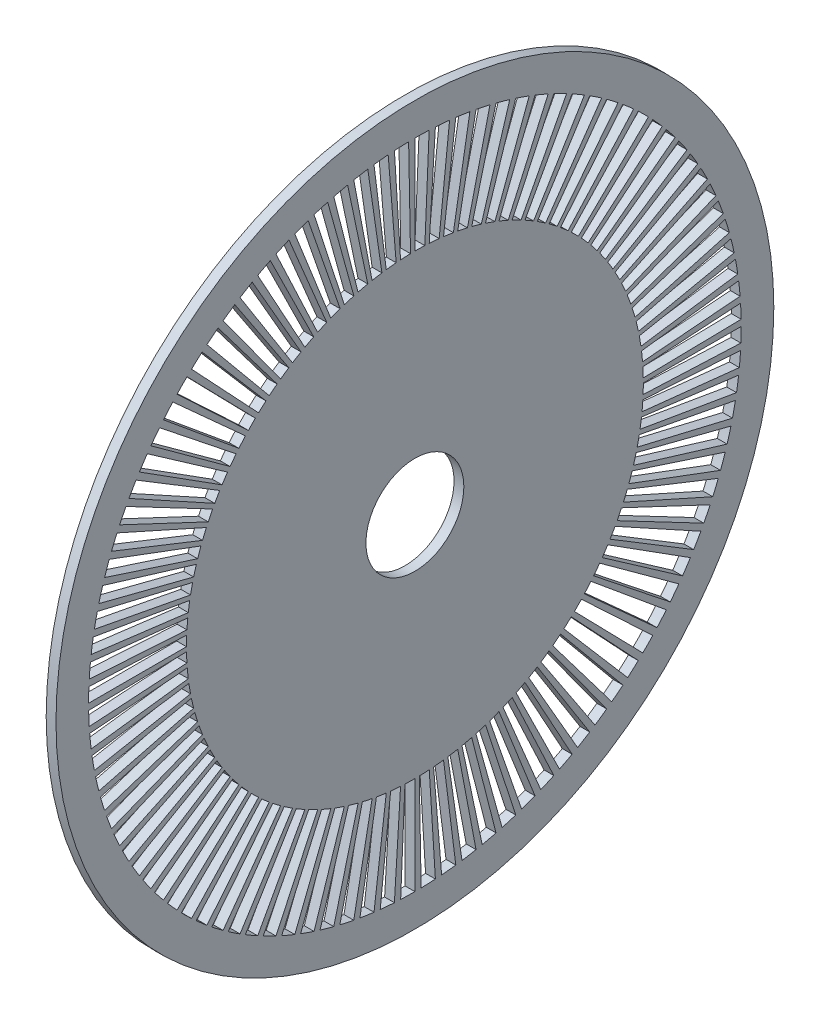
SolidWorks part; units mm, degrees
material "AISI 1020"
ref_plane "Plan de face" through (0, 0, 0) normal (0, 0, 1) x (1, 0, 0)
ref_plane "Plan de dessus" through (0, 0, 0) normal (0, 1, 0) x (1, 0, 0)
ref_plane "Plan de droite" through (0, 0, 0) normal (1, 0, 0) x (0, 0, -1)
sketch "Esquisse1" plane through (0, 0, 0) normal (1, 0, 0) x (0, 0, -1)
  line L0 (0, 0) -> (0, 11) construction
  line L1 (0, 0) -> (0.6907, 10.9783) construction
  line L2 (0, 7) -> (0, 10)
  line L3 (0.3053, 6.9933) -> (0.4362, 9.9905)
  line L4 (0, 0) -> (0.4798, 10.9895) construction
  line L5 (0.7438, 6.9604) -> (1.0626, 9.9434)
  line L6 (0.4395, 6.9862) -> (0.6279, 9.9803)
  line L7 (1.1794, 6.8999) -> (1.6849, 9.857)
  line L8 (0.8773, 6.9448) -> (1.2533, 9.9211)
  line L9 (1.6103, 6.8123) -> (2.3005, 9.7318)
  line L10 (1.3117, 6.876) -> (1.8738, 9.8229)
  line L11 (2.0349, 6.6977) -> (2.907, 9.5681)
  line L12 (1.7408, 6.7801) -> (2.4869, 9.6858)
  line L13 (2.4515, 6.5567) -> (3.5021, 9.3667)
  line L14 (2.1631, 6.6574) -> (3.0902, 9.5106)
  line L15 (2.8583, 6.3898) -> (4.0833, 9.1283)
  line L16 (2.5769, 6.5084) -> (3.6812, 9.2978)
  line L17 (3.2539, 6.1978) -> (4.6484, 8.8539)
  line L18 (2.9805, 6.3338) -> (4.2578, 9.0483)
  line L19 (3.6366, 5.9812) -> (5.1952, 8.5446)
  line L20 (3.3723, 6.1341) -> (4.8175, 8.7631)
  line L21 (4.005, 5.7411) -> (5.7215, 8.2015)
  line L22 (3.7508, 5.9103) -> (5.3583, 8.4433)
  line L23 (4.3576, 5.4783) -> (6.2251, 7.8261)
  line L24 (4.1145, 5.6631) -> (5.8779, 8.0902)
  line L25 (4.693, 5.1938) -> (6.7043, 7.4198)
  line L26 (4.462, 5.3936) -> (6.3742, 7.7051)
  line L27 (5.0098, 4.8889) -> (7.1569, 6.9842)
  line L28 (4.7918, 5.1028) -> (6.8455, 7.2897)
  line L29 (5.3069, 4.5647) -> (7.5813, 6.521)
  line L30 (5.1028, 4.7918) -> (7.2897, 6.8455)
  line L31 (5.5831, 4.2225) -> (7.9758, 6.0321)
  line L32 (5.3936, 4.462) -> (7.7051, 6.3742)
  line L33 (5.8372, 3.8636) -> (8.3389, 5.5194)
  line L34 (5.6631, 4.1145) -> (8.0902, 5.8779)
  line L35 (6.0683, 3.4894) -> (8.669, 4.9849)
  line L36 (5.9103, 3.7508) -> (8.4433, 5.3583)
  line L37 (6.2754, 3.1015) -> (8.9649, 4.4307)
  line L38 (6.1341, 3.3723) -> (8.7631, 4.8175)
  line L39 (6.4578, 2.7013) -> (9.2254, 3.8591)
  line L40 (6.3338, 2.9805) -> (9.0483, 4.2578)
  line L41 (6.6146, 2.2905) -> (9.4495, 3.2722)
  line L42 (6.5084, 2.5769) -> (9.2978, 3.6812)
  line L43 (6.7454, 1.8707) -> (9.6363, 2.6724)
  line L44 (6.6574, 2.1631) -> (9.5106, 3.0902)
  line L45 (6.8496, 1.4434) -> (9.7851, 2.062)
  line L46 (6.7801, 1.7408) -> (9.6858, 2.4869)
  line L47 (6.9267, 1.0105) -> (9.8953, 1.4436)
  line L48 (6.876, 1.3117) -> (9.8229, 1.8738)
  line L49 (6.9765, 0.5736) -> (9.9664, 0.8194)
  line L50 (6.9448, 0.8773) -> (9.9211, 1.2533)
  line L51 (6.9987, 0.1344) -> (9.9982, 0.192)
  line L52 (6.9862, 0.4395) -> (9.9803, 0.6279)
  line L53 (6.9933, -0.3053) -> (9.9905, -0.4362)
  line L54 (7, 0) -> (10, 0)
  line L55 (6.9604, -0.7438) -> (9.9434, -1.0626)
  line L56 (6.9862, -0.4395) -> (9.9803, -0.6279)
  line L57 (6.8999, -1.1794) -> (9.857, -1.6849)
  line L58 (6.9448, -0.8773) -> (9.9211, -1.2533)
  line L59 (6.8123, -1.6103) -> (9.7318, -2.3005)
  line L60 (6.876, -1.3117) -> (9.8229, -1.8738)
  line L61 (6.6977, -2.0349) -> (9.5681, -2.907)
  line L62 (6.7801, -1.7408) -> (9.6858, -2.4869)
  line L63 (6.5567, -2.4515) -> (9.3667, -3.5021)
  line L64 (6.6574, -2.1631) -> (9.5106, -3.0902)
  line L65 (6.3898, -2.8583) -> (9.1283, -4.0833)
  line L66 (6.5084, -2.5769) -> (9.2978, -3.6812)
  line L67 (6.1978, -3.2539) -> (8.8539, -4.6484)
  line L68 (6.3338, -2.9805) -> (9.0483, -4.2578)
  line L69 (5.9812, -3.6366) -> (8.5446, -5.1952)
  line L70 (6.1341, -3.3723) -> (8.7631, -4.8175)
  line L71 (5.7411, -4.005) -> (8.2015, -5.7215)
  line L72 (5.9103, -3.7508) -> (8.4433, -5.3583)
  line L73 (5.4783, -4.3576) -> (7.8261, -6.2251)
  line L74 (5.6631, -4.1145) -> (8.0902, -5.8779)
  line L75 (5.1938, -4.693) -> (7.4198, -6.7043)
  line L76 (5.3936, -4.462) -> (7.7051, -6.3742)
  line L77 (4.8889, -5.0098) -> (6.9842, -7.1569)
  line L78 (5.1028, -4.7918) -> (7.2897, -6.8455)
  line L79 (4.5647, -5.3069) -> (6.521, -7.5813)
  line L80 (4.7918, -5.1028) -> (6.8455, -7.2897)
  line L81 (4.2225, -5.5831) -> (6.0321, -7.9758)
  line L82 (4.462, -5.3936) -> (6.3742, -7.7051)
  line L83 (3.8636, -5.8372) -> (5.5194, -8.3389)
  line L84 (4.1145, -5.6631) -> (5.8779, -8.0902)
  line L85 (3.4894, -6.0683) -> (4.9849, -8.669)
  line L86 (3.7508, -5.9103) -> (5.3583, -8.4433)
  line L87 (3.1015, -6.2754) -> (4.4307, -8.9649)
  line L88 (3.3723, -6.1341) -> (4.8175, -8.7631)
  line L89 (2.7013, -6.4578) -> (3.8591, -9.2254)
  line L90 (2.9805, -6.3338) -> (4.2578, -9.0483)
  line L91 (2.2905, -6.6146) -> (3.2722, -9.4495)
  line L92 (2.5769, -6.5084) -> (3.6812, -9.2978)
  line L93 (1.8707, -6.7454) -> (2.6724, -9.6363)
  line L94 (2.1631, -6.6574) -> (3.0902, -9.5106)
  line L95 (1.4434, -6.8496) -> (2.062, -9.7851)
  line L96 (1.7408, -6.7801) -> (2.4869, -9.6858)
  line L97 (1.0105, -6.9267) -> (1.4436, -9.8953)
  line L98 (1.3117, -6.876) -> (1.8738, -9.8229)
  line L99 (0.5736, -6.9765) -> (0.8194, -9.9664)
  line L100 (0.8773, -6.9448) -> (1.2533, -9.9211)
  line L101 (0.1344, -6.9987) -> (0.192, -9.9982)
  line L102 (0.4395, -6.9862) -> (0.6279, -9.9803)
  line L103 (-0.3053, -6.9933) -> (-0.4362, -9.9905)
  line L104 (0, -7) -> (0, -10)
  line L105 (-0.7438, -6.9604) -> (-1.0626, -9.9434)
  line L106 (-0.4395, -6.9862) -> (-0.6279, -9.9803)
  line L107 (-1.1794, -6.8999) -> (-1.6849, -9.857)
  line L108 (-0.8773, -6.9448) -> (-1.2533, -9.9211)
  line L109 (-1.6103, -6.8123) -> (-2.3005, -9.7318)
  line L110 (-1.3117, -6.876) -> (-1.8738, -9.8229)
  line L111 (-2.0349, -6.6977) -> (-2.907, -9.5681)
  line L112 (-1.7408, -6.7801) -> (-2.4869, -9.6858)
  line L113 (-2.4515, -6.5567) -> (-3.5021, -9.3667)
  line L114 (-2.1631, -6.6574) -> (-3.0902, -9.5106)
  line L115 (-2.8583, -6.3898) -> (-4.0833, -9.1283)
  line L116 (-2.5769, -6.5084) -> (-3.6812, -9.2978)
  line L117 (-3.2539, -6.1978) -> (-4.6484, -8.8539)
  line L118 (-2.9805, -6.3338) -> (-4.2578, -9.0483)
  line L119 (-3.6366, -5.9812) -> (-5.1952, -8.5446)
  line L120 (-3.3723, -6.1341) -> (-4.8175, -8.7631)
  line L121 (-4.005, -5.7411) -> (-5.7215, -8.2015)
  line L122 (-3.7508, -5.9103) -> (-5.3583, -8.4433)
  line L123 (-4.3576, -5.4783) -> (-6.2251, -7.8261)
  line L124 (-4.1145, -5.6631) -> (-5.8779, -8.0902)
  line L125 (-4.693, -5.1938) -> (-6.7043, -7.4198)
  line L126 (-4.462, -5.3936) -> (-6.3742, -7.7051)
  line L127 (-5.0098, -4.8889) -> (-7.1569, -6.9842)
  line L128 (-4.7918, -5.1028) -> (-6.8455, -7.2897)
  line L129 (-5.3069, -4.5647) -> (-7.5813, -6.521)
  line L130 (-5.1028, -4.7918) -> (-7.2897, -6.8455)
  line L131 (-5.5831, -4.2225) -> (-7.9758, -6.0321)
  line L132 (-5.3936, -4.462) -> (-7.7051, -6.3742)
  line L133 (-5.8372, -3.8636) -> (-8.3389, -5.5194)
  line L134 (-5.6631, -4.1145) -> (-8.0902, -5.8779)
  line L135 (-6.0683, -3.4894) -> (-8.669, -4.9849)
  line L136 (-5.9103, -3.7508) -> (-8.4433, -5.3583)
  line L137 (-6.2754, -3.1015) -> (-8.9649, -4.4307)
  line L138 (-6.1341, -3.3723) -> (-8.7631, -4.8175)
  line L139 (-6.4578, -2.7013) -> (-9.2254, -3.8591)
  line L140 (-6.3338, -2.9805) -> (-9.0483, -4.2578)
  line L141 (-6.6146, -2.2905) -> (-9.4495, -3.2722)
  line L142 (-6.5084, -2.5769) -> (-9.2978, -3.6812)
  line L143 (-6.7454, -1.8707) -> (-9.6363, -2.6724)
  line L144 (-6.6574, -2.1631) -> (-9.5106, -3.0902)
  line L145 (-6.8496, -1.4434) -> (-9.7851, -2.062)
  line L146 (-6.7801, -1.7408) -> (-9.6858, -2.4869)
  line L147 (-6.9267, -1.0105) -> (-9.8953, -1.4436)
  line L148 (-6.876, -1.3117) -> (-9.8229, -1.8738)
  line L149 (-6.9765, -0.5736) -> (-9.9664, -0.8194)
  line L150 (-6.9448, -0.8773) -> (-9.9211, -1.2533)
  line L151 (-6.9987, -0.1344) -> (-9.9982, -0.192)
  line L152 (-6.9862, -0.4395) -> (-9.9803, -0.6279)
  line L153 (-6.9933, 0.3053) -> (-9.9905, 0.4362)
  line L154 (-7, 0) -> (-10, 0)
  line L155 (-6.9604, 0.7438) -> (-9.9434, 1.0626)
  line L156 (-6.9862, 0.4395) -> (-9.9803, 0.6279)
  line L157 (-6.8999, 1.1794) -> (-9.857, 1.6849)
  line L158 (-6.9448, 0.8773) -> (-9.9211, 1.2533)
  line L159 (-6.8123, 1.6103) -> (-9.7318, 2.3005)
  line L160 (-6.876, 1.3117) -> (-9.8229, 1.8738)
  line L161 (-6.6977, 2.0349) -> (-9.5681, 2.907)
  line L162 (-6.7801, 1.7408) -> (-9.6858, 2.4869)
  line L163 (-6.5567, 2.4515) -> (-9.3667, 3.5021)
  line L164 (-6.6574, 2.1631) -> (-9.5106, 3.0902)
  line L165 (-6.3898, 2.8583) -> (-9.1283, 4.0833)
  line L166 (-6.5084, 2.5769) -> (-9.2978, 3.6812)
  line L167 (-6.1978, 3.2539) -> (-8.8539, 4.6484)
  line L168 (-6.3338, 2.9805) -> (-9.0483, 4.2578)
  line L169 (-5.9812, 3.6366) -> (-8.5446, 5.1952)
  line L170 (-6.1341, 3.3723) -> (-8.7631, 4.8175)
  line L171 (-5.7411, 4.005) -> (-8.2015, 5.7215)
  line L172 (-5.9103, 3.7508) -> (-8.4433, 5.3583)
  line L173 (-5.4783, 4.3576) -> (-7.8261, 6.2251)
  line L174 (-5.6631, 4.1145) -> (-8.0902, 5.8779)
  line L175 (-5.1938, 4.693) -> (-7.4198, 6.7043)
  line L176 (-5.3936, 4.462) -> (-7.7051, 6.3742)
  line L177 (-4.8889, 5.0098) -> (-6.9842, 7.1569)
  line L178 (-5.1028, 4.7918) -> (-7.2897, 6.8455)
  line L179 (-4.5647, 5.3069) -> (-6.521, 7.5813)
  line L180 (-4.7918, 5.1028) -> (-6.8455, 7.2897)
  line L181 (-4.2225, 5.5831) -> (-6.0321, 7.9758)
  line L182 (-4.462, 5.3936) -> (-6.3742, 7.7051)
  line L183 (-3.8636, 5.8372) -> (-5.5194, 8.3389)
  line L184 (-4.1145, 5.6631) -> (-5.8779, 8.0902)
  line L185 (-3.4894, 6.0683) -> (-4.9849, 8.669)
  line L186 (-3.7508, 5.9103) -> (-5.3583, 8.4433)
  line L187 (-3.1015, 6.2754) -> (-4.4307, 8.9649)
  line L188 (-3.3723, 6.1341) -> (-4.8175, 8.7631)
  line L189 (-2.7013, 6.4578) -> (-3.8591, 9.2254)
  line L190 (-2.9805, 6.3338) -> (-4.2578, 9.0483)
  line L191 (-2.2905, 6.6146) -> (-3.2722, 9.4495)
  line L192 (-2.5769, 6.5084) -> (-3.6812, 9.2978)
  line L193 (-1.8707, 6.7454) -> (-2.6724, 9.6363)
  line L194 (-2.1631, 6.6574) -> (-3.0902, 9.5106)
  line L195 (-1.4434, 6.8496) -> (-2.062, 9.7851)
  line L196 (-1.7408, 6.7801) -> (-2.4869, 9.6858)
  line L197 (-1.0105, 6.9267) -> (-1.4436, 9.8953)
  line L198 (-1.3117, 6.876) -> (-1.8738, 9.8229)
  line L199 (-0.5736, 6.9765) -> (-0.8194, 9.9664)
  line L200 (-0.8773, 6.9448) -> (-1.2533, 9.9211)
  line L201 (-0.1344, 6.9987) -> (-0.192, 9.9982)
  line L202 (-0.4395, 6.9862) -> (-0.6279, 9.9803)
  circle A0 centre (0, 0) radius 11
  circle A1 centre (0, 0) radius 1.5
  arc A2 (0, 10) -> (0.4362, 9.9905) centre (0, 0) cw
  arc A3 (0, 7) -> (0.3053, 6.9933) centre (0, 0) cw
  arc A4 (0.6279, 9.9803) -> (1.0626, 9.9434) centre (0, 0) cw
  arc A5 (0.4395, 6.9862) -> (0.7438, 6.9604) centre (0, 0) cw
  arc A6 (1.2533, 9.9211) -> (1.6849, 9.857) centre (0, 0) cw
  arc A7 (0.8773, 6.9448) -> (1.1794, 6.8999) centre (0, 0) cw
  arc A8 (1.8738, 9.8229) -> (2.3005, 9.7318) centre (0, 0) cw
  arc A9 (1.3117, 6.876) -> (1.6103, 6.8123) centre (0, 0) cw
  arc A10 (2.4869, 9.6858) -> (2.907, 9.5681) centre (0, 0) cw
  arc A11 (1.7408, 6.7801) -> (2.0349, 6.6977) centre (0, 0) cw
  arc A12 (3.0902, 9.5106) -> (3.5021, 9.3667) centre (0, 0) cw
  arc A13 (2.1631, 6.6574) -> (2.4515, 6.5567) centre (0, 0) cw
  arc A14 (3.6812, 9.2978) -> (4.0833, 9.1283) centre (0, 0) cw
  arc A15 (2.5769, 6.5084) -> (2.8583, 6.3898) centre (0, 0) cw
  arc A16 (4.2578, 9.0483) -> (4.6484, 8.8539) centre (0, 0) cw
  arc A17 (2.9805, 6.3338) -> (3.2539, 6.1978) centre (0, 0) cw
  arc A18 (4.8175, 8.7631) -> (5.1952, 8.5446) centre (0, 0) cw
  arc A19 (3.3723, 6.1341) -> (3.6366, 5.9812) centre (0, 0) cw
  arc A20 (5.3583, 8.4433) -> (5.7215, 8.2015) centre (0, 0) cw
  arc A21 (3.7508, 5.9103) -> (4.005, 5.7411) centre (0, 0) cw
  arc A22 (5.8779, 8.0902) -> (6.2251, 7.8261) centre (0, 0) cw
  arc A23 (4.1145, 5.6631) -> (4.3576, 5.4783) centre (0, 0) cw
  arc A24 (6.3742, 7.7051) -> (6.7043, 7.4198) centre (0, 0) cw
  arc A25 (4.462, 5.3936) -> (4.693, 5.1938) centre (0, 0) cw
  arc A26 (6.8455, 7.2897) -> (7.1569, 6.9842) centre (0, 0) cw
  arc A27 (4.7918, 5.1028) -> (5.0098, 4.8889) centre (0, 0) cw
  arc A28 (7.2897, 6.8455) -> (7.5813, 6.521) centre (0, 0) cw
  arc A29 (5.1028, 4.7918) -> (5.3069, 4.5647) centre (0, 0) cw
  arc A30 (7.7051, 6.3742) -> (7.9758, 6.0321) centre (0, 0) cw
  arc A31 (5.3936, 4.462) -> (5.5831, 4.2225) centre (0, 0) cw
  arc A32 (8.0902, 5.8779) -> (8.3389, 5.5194) centre (0, 0) cw
  arc A33 (5.6631, 4.1145) -> (5.8372, 3.8636) centre (0, 0) cw
  arc A34 (8.4433, 5.3583) -> (8.669, 4.9849) centre (0, 0) cw
  arc A35 (5.9103, 3.7508) -> (6.0683, 3.4894) centre (0, 0) cw
  arc A36 (8.7631, 4.8175) -> (8.9649, 4.4307) centre (0, 0) cw
  arc A37 (6.1341, 3.3723) -> (6.2754, 3.1015) centre (0, 0) cw
  arc A38 (9.0483, 4.2578) -> (9.2254, 3.8591) centre (0, 0) cw
  arc A39 (6.3338, 2.9805) -> (6.4578, 2.7013) centre (0, 0) cw
  arc A40 (9.2978, 3.6812) -> (9.4495, 3.2722) centre (0, 0) cw
  arc A41 (6.5084, 2.5769) -> (6.6146, 2.2905) centre (0, 0) cw
  arc A42 (9.5106, 3.0902) -> (9.6363, 2.6724) centre (0, 0) cw
  arc A43 (6.6574, 2.1631) -> (6.7454, 1.8707) centre (0, 0) cw
  arc A44 (9.6858, 2.4869) -> (9.7851, 2.062) centre (0, 0) cw
  arc A45 (6.7801, 1.7408) -> (6.8496, 1.4434) centre (0, 0) cw
  arc A46 (9.8229, 1.8738) -> (9.8953, 1.4436) centre (0, 0) cw
  arc A47 (6.876, 1.3117) -> (6.9267, 1.0105) centre (0, 0) cw
  arc A48 (9.9211, 1.2533) -> (9.9664, 0.8194) centre (0, 0) cw
  arc A49 (6.9448, 0.8773) -> (6.9765, 0.5736) centre (0, 0) cw
  arc A50 (9.9803, 0.6279) -> (9.9982, 0.192) centre (0, 0) cw
  arc A51 (6.9862, 0.4395) -> (6.9987, 0.1344) centre (0, 0) cw
  arc A52 (10, 0) -> (9.9905, -0.4362) centre (0, 0) cw
  arc A53 (7, 0) -> (6.9933, -0.3053) centre (0, 0) cw
  arc A54 (9.9803, -0.6279) -> (9.9434, -1.0626) centre (0, 0) cw
  arc A55 (6.9862, -0.4395) -> (6.9604, -0.7438) centre (0, 0) cw
  arc A56 (9.9211, -1.2533) -> (9.857, -1.6849) centre (0, 0) cw
  arc A57 (6.9448, -0.8773) -> (6.8999, -1.1794) centre (0, 0) cw
  arc A58 (9.8229, -1.8738) -> (9.7318, -2.3005) centre (0, 0) cw
  arc A59 (6.876, -1.3117) -> (6.8123, -1.6103) centre (0, 0) cw
  arc A60 (9.6858, -2.4869) -> (9.5681, -2.907) centre (0, 0) cw
  arc A61 (6.7801, -1.7408) -> (6.6977, -2.0349) centre (0, 0) cw
  arc A62 (9.5106, -3.0902) -> (9.3667, -3.5021) centre (0, 0) cw
  arc A63 (6.6574, -2.1631) -> (6.5567, -2.4515) centre (0, 0) cw
  arc A64 (9.2978, -3.6812) -> (9.1283, -4.0833) centre (0, 0) cw
  arc A65 (6.5084, -2.5769) -> (6.3898, -2.8583) centre (0, 0) cw
  arc A66 (9.0483, -4.2578) -> (8.8539, -4.6484) centre (0, 0) cw
  arc A67 (6.3338, -2.9805) -> (6.1978, -3.2539) centre (0, 0) cw
  arc A68 (8.7631, -4.8175) -> (8.5446, -5.1952) centre (0, 0) cw
  arc A69 (6.1341, -3.3723) -> (5.9812, -3.6366) centre (0, 0) cw
  arc A70 (8.4433, -5.3583) -> (8.2015, -5.7215) centre (0, 0) cw
  arc A71 (5.9103, -3.7508) -> (5.7411, -4.005) centre (0, 0) cw
  arc A72 (8.0902, -5.8779) -> (7.8261, -6.2251) centre (0, 0) cw
  arc A73 (5.6631, -4.1145) -> (5.4783, -4.3576) centre (0, 0) cw
  arc A74 (7.7051, -6.3742) -> (7.4198, -6.7043) centre (0, 0) cw
  arc A75 (5.3936, -4.462) -> (5.1938, -4.693) centre (0, 0) cw
  arc A76 (7.2897, -6.8455) -> (6.9842, -7.1569) centre (0, 0) cw
  arc A77 (5.1028, -4.7918) -> (4.8889, -5.0098) centre (0, 0) cw
  arc A78 (6.8455, -7.2897) -> (6.521, -7.5813) centre (0, 0) cw
  arc A79 (4.7918, -5.1028) -> (4.5647, -5.3069) centre (0, 0) cw
  arc A80 (6.3742, -7.7051) -> (6.0321, -7.9758) centre (0, 0) cw
  arc A81 (4.462, -5.3936) -> (4.2225, -5.5831) centre (0, 0) cw
  arc A82 (5.8779, -8.0902) -> (5.5194, -8.3389) centre (0, 0) cw
  arc A83 (4.1145, -5.6631) -> (3.8636, -5.8372) centre (0, 0) cw
  arc A84 (5.3583, -8.4433) -> (4.9849, -8.669) centre (0, 0) cw
  arc A85 (3.7508, -5.9103) -> (3.4894, -6.0683) centre (0, 0) cw
  arc A86 (4.8175, -8.7631) -> (4.4307, -8.9649) centre (0, 0) cw
  arc A87 (3.3723, -6.1341) -> (3.1015, -6.2754) centre (0, 0) cw
  arc A88 (4.2578, -9.0483) -> (3.8591, -9.2254) centre (0, 0) cw
  arc A89 (2.9805, -6.3338) -> (2.7013, -6.4578) centre (0, 0) cw
  arc A90 (3.6812, -9.2978) -> (3.2722, -9.4495) centre (0, 0) cw
  arc A91 (2.5769, -6.5084) -> (2.2905, -6.6146) centre (0, 0) cw
  arc A92 (3.0902, -9.5106) -> (2.6724, -9.6363) centre (0, 0) cw
  arc A93 (2.1631, -6.6574) -> (1.8707, -6.7454) centre (0, 0) cw
  arc A94 (2.4869, -9.6858) -> (2.062, -9.7851) centre (0, 0) cw
  arc A95 (1.7408, -6.7801) -> (1.4434, -6.8496) centre (0, 0) cw
  arc A96 (1.8738, -9.8229) -> (1.4436, -9.8953) centre (0, 0) cw
  arc A97 (1.3117, -6.876) -> (1.0105, -6.9267) centre (0, 0) cw
  arc A98 (1.2533, -9.9211) -> (0.8194, -9.9664) centre (0, 0) cw
  arc A99 (0.8773, -6.9448) -> (0.5736, -6.9765) centre (0, 0) cw
  arc A100 (0.6279, -9.9803) -> (0.192, -9.9982) centre (0, 0) cw
  arc A101 (0.4395, -6.9862) -> (0.1344, -6.9987) centre (0, 0) cw
  arc A102 (0, -10) -> (-0.4362, -9.9905) centre (0, 0) cw
  arc A103 (0, -7) -> (-0.3053, -6.9933) centre (0, 0) cw
  arc A104 (-0.6279, -9.9803) -> (-1.0626, -9.9434) centre (0, 0) cw
  arc A105 (-0.4395, -6.9862) -> (-0.7438, -6.9604) centre (0, 0) cw
  arc A106 (-1.2533, -9.9211) -> (-1.6849, -9.857) centre (0, 0) cw
  arc A107 (-0.8773, -6.9448) -> (-1.1794, -6.8999) centre (0, 0) cw
  arc A108 (-1.8738, -9.8229) -> (-2.3005, -9.7318) centre (0, 0) cw
  arc A109 (-1.3117, -6.876) -> (-1.6103, -6.8123) centre (0, 0) cw
  arc A110 (-2.4869, -9.6858) -> (-2.907, -9.5681) centre (0, 0) cw
  arc A111 (-1.7408, -6.7801) -> (-2.0349, -6.6977) centre (0, 0) cw
  arc A112 (-3.0902, -9.5106) -> (-3.5021, -9.3667) centre (0, 0) cw
  arc A113 (-2.1631, -6.6574) -> (-2.4515, -6.5567) centre (0, 0) cw
  arc A114 (-3.6812, -9.2978) -> (-4.0833, -9.1283) centre (0, 0) cw
  arc A115 (-2.5769, -6.5084) -> (-2.8583, -6.3898) centre (0, 0) cw
  arc A116 (-4.2578, -9.0483) -> (-4.6484, -8.8539) centre (0, 0) cw
  arc A117 (-2.9805, -6.3338) -> (-3.2539, -6.1978) centre (0, 0) cw
  arc A118 (-4.8175, -8.7631) -> (-5.1952, -8.5446) centre (0, 0) cw
  arc A119 (-3.3723, -6.1341) -> (-3.6366, -5.9812) centre (0, 0) cw
  arc A120 (-5.3583, -8.4433) -> (-5.7215, -8.2015) centre (0, 0) cw
  arc A121 (-3.7508, -5.9103) -> (-4.005, -5.7411) centre (0, 0) cw
  arc A122 (-5.8779, -8.0902) -> (-6.2251, -7.8261) centre (0, 0) cw
  arc A123 (-4.1145, -5.6631) -> (-4.3576, -5.4783) centre (0, 0) cw
  arc A124 (-6.3742, -7.7051) -> (-6.7043, -7.4198) centre (0, 0) cw
  arc A125 (-4.462, -5.3936) -> (-4.693, -5.1938) centre (0, 0) cw
  arc A126 (-6.8455, -7.2897) -> (-7.1569, -6.9842) centre (0, 0) cw
  arc A127 (-4.7918, -5.1028) -> (-5.0098, -4.8889) centre (0, 0) cw
  arc A128 (-7.2897, -6.8455) -> (-7.5813, -6.521) centre (0, 0) cw
  arc A129 (-5.1028, -4.7918) -> (-5.3069, -4.5647) centre (0, 0) cw
  arc A130 (-7.7051, -6.3742) -> (-7.9758, -6.0321) centre (0, 0) cw
  arc A131 (-5.3936, -4.462) -> (-5.5831, -4.2225) centre (0, 0) cw
  arc A132 (-8.0902, -5.8779) -> (-8.3389, -5.5194) centre (0, 0) cw
  arc A133 (-5.6631, -4.1145) -> (-5.8372, -3.8636) centre (0, 0) cw
  arc A134 (-8.4433, -5.3583) -> (-8.669, -4.9849) centre (0, 0) cw
  arc A135 (-5.9103, -3.7508) -> (-6.0683, -3.4894) centre (0, 0) cw
  arc A136 (-8.7631, -4.8175) -> (-8.9649, -4.4307) centre (0, 0) cw
  arc A137 (-6.1341, -3.3723) -> (-6.2754, -3.1015) centre (0, 0) cw
  arc A138 (-9.0483, -4.2578) -> (-9.2254, -3.8591) centre (0, 0) cw
  arc A139 (-6.3338, -2.9805) -> (-6.4578, -2.7013) centre (0, 0) cw
  arc A140 (-9.2978, -3.6812) -> (-9.4495, -3.2722) centre (0, 0) cw
  arc A141 (-6.5084, -2.5769) -> (-6.6146, -2.2905) centre (0, 0) cw
  arc A142 (-9.5106, -3.0902) -> (-9.6363, -2.6724) centre (0, 0) cw
  arc A143 (-6.6574, -2.1631) -> (-6.7454, -1.8707) centre (0, 0) cw
  arc A144 (-9.6858, -2.4869) -> (-9.7851, -2.062) centre (0, 0) cw
  arc A145 (-6.7801, -1.7408) -> (-6.8496, -1.4434) centre (0, 0) cw
  arc A146 (-9.8229, -1.8738) -> (-9.8953, -1.4436) centre (0, 0) cw
  arc A147 (-6.876, -1.3117) -> (-6.9267, -1.0105) centre (0, 0) cw
  arc A148 (-9.9211, -1.2533) -> (-9.9664, -0.8194) centre (0, 0) cw
  arc A149 (-6.9448, -0.8773) -> (-6.9765, -0.5736) centre (0, 0) cw
  arc A150 (-9.9803, -0.6279) -> (-9.9982, -0.192) centre (0, 0) cw
  arc A151 (-6.9862, -0.4395) -> (-6.9987, -0.1344) centre (0, 0) cw
  arc A152 (-10, 0) -> (-9.9905, 0.4362) centre (0, 0) cw
  arc A153 (-7, 0) -> (-6.9933, 0.3053) centre (0, 0) cw
  arc A154 (-9.9803, 0.6279) -> (-9.9434, 1.0626) centre (0, 0) cw
  arc A155 (-6.9862, 0.4395) -> (-6.9604, 0.7438) centre (0, 0) cw
  arc A156 (-9.9211, 1.2533) -> (-9.857, 1.6849) centre (0, 0) cw
  arc A157 (-6.9448, 0.8773) -> (-6.8999, 1.1794) centre (0, 0) cw
  arc A158 (-9.8229, 1.8738) -> (-9.7318, 2.3005) centre (0, 0) cw
  arc A159 (-6.876, 1.3117) -> (-6.8123, 1.6103) centre (0, 0) cw
  arc A160 (-9.6858, 2.4869) -> (-9.5681, 2.907) centre (0, 0) cw
  arc A161 (-6.7801, 1.7408) -> (-6.6977, 2.0349) centre (0, 0) cw
  arc A162 (-9.5106, 3.0902) -> (-9.3667, 3.5021) centre (0, 0) cw
  arc A163 (-6.6574, 2.1631) -> (-6.5567, 2.4515) centre (0, 0) cw
  arc A164 (-9.2978, 3.6812) -> (-9.1283, 4.0833) centre (0, 0) cw
  arc A165 (-6.5084, 2.5769) -> (-6.3898, 2.8583) centre (0, 0) cw
  arc A166 (-9.0483, 4.2578) -> (-8.8539, 4.6484) centre (0, 0) cw
  arc A167 (-6.3338, 2.9805) -> (-6.1978, 3.2539) centre (0, 0) cw
  arc A168 (-8.7631, 4.8175) -> (-8.5446, 5.1952) centre (0, 0) cw
  arc A169 (-6.1341, 3.3723) -> (-5.9812, 3.6366) centre (0, 0) cw
  arc A170 (-8.4433, 5.3583) -> (-8.2015, 5.7215) centre (0, 0) cw
  arc A171 (-5.9103, 3.7508) -> (-5.7411, 4.005) centre (0, 0) cw
  arc A172 (-8.0902, 5.8779) -> (-7.8261, 6.2251) centre (0, 0) cw
  arc A173 (-5.6631, 4.1145) -> (-5.4783, 4.3576) centre (0, 0) cw
  arc A174 (-7.7051, 6.3742) -> (-7.4198, 6.7043) centre (0, 0) cw
  arc A175 (-5.3936, 4.462) -> (-5.1938, 4.693) centre (0, 0) cw
  arc A176 (-7.2897, 6.8455) -> (-6.9842, 7.1569) centre (0, 0) cw
  arc A177 (-5.1028, 4.7918) -> (-4.8889, 5.0098) centre (0, 0) cw
  arc A178 (-6.8455, 7.2897) -> (-6.521, 7.5813) centre (0, 0) cw
  arc A179 (-4.7918, 5.1028) -> (-4.5647, 5.3069) centre (0, 0) cw
  arc A180 (-6.3742, 7.7051) -> (-6.0321, 7.9758) centre (0, 0) cw
  arc A181 (-4.462, 5.3936) -> (-4.2225, 5.5831) centre (0, 0) cw
  arc A182 (-5.8779, 8.0902) -> (-5.5194, 8.3389) centre (0, 0) cw
  arc A183 (-4.1145, 5.6631) -> (-3.8636, 5.8372) centre (0, 0) cw
  arc A184 (-5.3583, 8.4433) -> (-4.9849, 8.669) centre (0, 0) cw
  arc A185 (-3.7508, 5.9103) -> (-3.4894, 6.0683) centre (0, 0) cw
  arc A186 (-4.8175, 8.7631) -> (-4.4307, 8.9649) centre (0, 0) cw
  arc A187 (-3.3723, 6.1341) -> (-3.1015, 6.2754) centre (0, 0) cw
  arc A188 (-4.2578, 9.0483) -> (-3.8591, 9.2254) centre (0, 0) cw
  arc A189 (-2.9805, 6.3338) -> (-2.7013, 6.4578) centre (0, 0) cw
  arc A190 (-3.6812, 9.2978) -> (-3.2722, 9.4495) centre (0, 0) cw
  arc A191 (-2.5769, 6.5084) -> (-2.2905, 6.6146) centre (0, 0) cw
  arc A192 (-3.0902, 9.5106) -> (-2.6724, 9.6363) centre (0, 0) cw
  arc A193 (-2.1631, 6.6574) -> (-1.8707, 6.7454) centre (0, 0) cw
  arc A194 (-2.4869, 9.6858) -> (-2.062, 9.7851) centre (0, 0) cw
  arc A195 (-1.7408, 6.7801) -> (-1.4434, 6.8496) centre (0, 0) cw
  arc A196 (-1.8738, 9.8229) -> (-1.4436, 9.8953) centre (0, 0) cw
  arc A197 (-1.3117, 6.876) -> (-1.0105, 6.9267) centre (0, 0) cw
  arc A198 (-1.2533, 9.9211) -> (-0.8194, 9.9664) centre (0, 0) cw
  arc A199 (-0.8773, 6.9448) -> (-0.5736, 6.9765) centre (0, 0) cw
  arc A200 (-0.6279, 9.9803) -> (-0.192, 9.9982) centre (0, 0) cw
  arc A201 (-0.4395, 6.9862) -> (-0.1344, 6.9987) centre (0, 0) cw
  point P409 (0, 0)
  dimension "D1" = 22
  dimension "D2" = 3
  dimension "D4" = 1
  dimension "D3" = 3.6
  dimension "D5" = 7
  dimension "D6" = 2.5
  dimension "D7" = 100
extrude "Boss.-Extru.1" add sketch "Esquisse1" along normal blind 0.3
